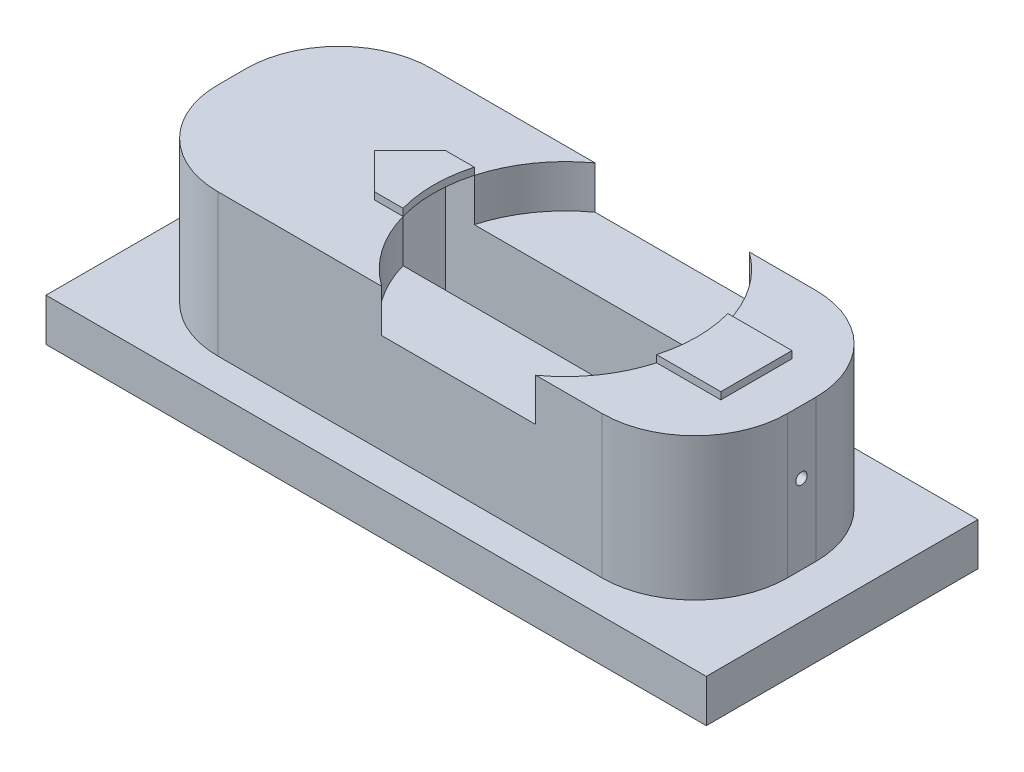
SolidWorks part; units mm, degrees
ref_plane "Front Plane" through (0, 0, 0) normal (0, 0, 1) x (1, 0, 0)
ref_plane "Top Plane" through (0, 0, 0) normal (0, 1, 0) x (1, 0, 0)
ref_plane "Right Plane" through (0, 0, 0) normal (1, 0, 0) x (0, 0, -1)
sketch "Sketch1" plane through (0, 0, 0) normal (0, 1, 0) x (1, 0, 0)
  line L1 (-40, -15) -> (40, -15)
  line L2 (-40, -15) -> (-40, 15)
  line L3 (-40, 15) -> (40, 15)
  line L4 (40, -15) -> (40, 15)
  line L5 (-40, -15) -> (40, 15) construction
  line L6 (-40, 15) -> (40, -15) construction
  point P0 (0, 0)
  dimension "D1" = 30
  dimension "D2" = 80
extrude "Boss-Extrude1" add sketch "Sketch1" along normal blind 60
sketch "Sketch2" plane through (0, 60, 0) normal (0, 1, 0) x (1, 0, 0)
  line L0 (-15, 5) -> (15, 5)
  line L3 (15, -5) -> (-15, -5)
  line L4 (-15, -5) -> (-20, 0)
  line L5 (-20, 0) -> (-15, 5)
  line L6 (15, 5) -> (33.657, 5)
  line L7 (33.657, 5) -> (33.657, -5)
  line L8 (33.657, -5) -> (15, -5)
  dimension "D1" = 15
  dimension "D2" = 15
  dimension "D3" = 15
  dimension "D4" = 15
  dimension "D5" = 5
  dimension "D6" = 5
extrude "Cut-Extrude1" cut sketch "Sketch2" against normal blind 75
sketch "Sketch3" plane through (-40, 0, 0) normal (-1, 0, 0) x (0, 0, 1)
  circle A0 centre (0, 51.112) radius 0.8
  dimension "D1" = 1.6
extrude "Cut-Extrude2" cut sketch "Sketch3" against normal through all and the other way through all
sketch "Sketch4" plane through (-40, 0, 0) normal (-1, 0, 0) x (0, 0, 1)
  circle A0 centre (0, 51.112) radius 1.5
  circle A1 centre (0, 51.112) radius 1.2
  dimension "D1" = 2.4
  dimension "D2" = 3
fillet "Fillet1" radius 13 4 edges at (40, 30, -15) (-40, 30, -15) (40, 30, 15) (-40, 30, 15)
sketch "Sketch9" plane through (40, 0, 0) normal (1, 0, 0) x (0, 0, -1)
  circle A0 centre (0, 51.112) radius 0.8
  circle A1 centre (0, 51.112) radius 1.2
  dimension "D1" = 2.4
ref_plane "Plane2" through (0, -10, 0) normal (0, -1, 0) x (-1, 0, 0)
sketch "Sketch15" plane through (0, -10, 0) normal (0, -1, 0) x (-1, 0, 0)
  line L1 (-41.9055, 15.8797) -> (41.7906, 15.8797)
  line L2 (-41.9055, 15.8797) -> (-41.9055, -15.8187)
  line L3 (-41.9055, -15.8187) -> (41.7906, -15.8187)
  line L4 (41.7906, 15.8797) -> (41.7906, -15.8187)
extrude "Cut-Extrude7" cut sketch "Sketch15" against normal blind 50
ref_plane "Plane3" through (0, 40, 0) normal (0, -1, 0) x (-1, 0, 0)
sketch "Sketch16" plane through (0, 40, 0) normal (0, -1, 0) x (-1, 0, 0)
  line L1 (-46.2811, 18.511) -> (46.4879, 18.511)
  line L2 (-46.2811, 18.511) -> (-46.2811, -19.6628)
  line L3 (-46.2811, -19.6628) -> (46.4879, -19.6628)
  line L4 (46.4879, 18.511) -> (46.4879, -19.6628)
  point P4 (0, 0)
  point P5 (47.7807, -19.6628)
  point P6 (-46.2811, 18.511)
extrude "Boss-Extrude4" add sketch "Sketch16" along normal blind 6
ref_plane "Plane4" through (0, 60, 0) normal (0, 1, 0) x (1, 0, 0)
sketch "Sketch18" plane through (0, 60, 0) normal (0, 1, 0) x (1, 0, 0)
  circle A0 centre (6.8285, 0) radius 18.5
  dimension "D1" = 37
sketch "Sketch19" plane through (0, 60, 0) normal (0, 1, 0) x (1, 0, 0)
  line L0 (33.657, 5) -> (-15, 5) construction
  line L1 (-15, -5) -> (33.657, -5) construction
  line L2 (-10.983, 5) -> (-15, 5)
  line L3 (-15, 5) -> (-20, 0)
  line L4 (-20, 0) -> (-15, -5)
  line L5 (-15, -5) -> (-10.983, -5)
  line L6 (-15, -5) -> (33.657, -5) construction
  line L7 (24.64, 5) -> (33.657, 5)
  line L8 (33.657, 5) -> (33.657, -5)
  line L9 (33.657, -5) -> (24.64, -5)
  arc A0 (-10.983, 5) -> (-10.983, -5) centre (6.8285, 0) ccw
  circle A1 centre (6.8285, 0) radius 18.5 construction
  arc A2 (24.64, 5) -> (24.64, -5) centre (6.8285, 0) cw
extrude "Cut-Extrude8" cut sketch "Sketch18" against normal blind 6 contours A0
extrude "Boss-Extrude5" add sketch "Sketch19" along normal blind 1 separate body
